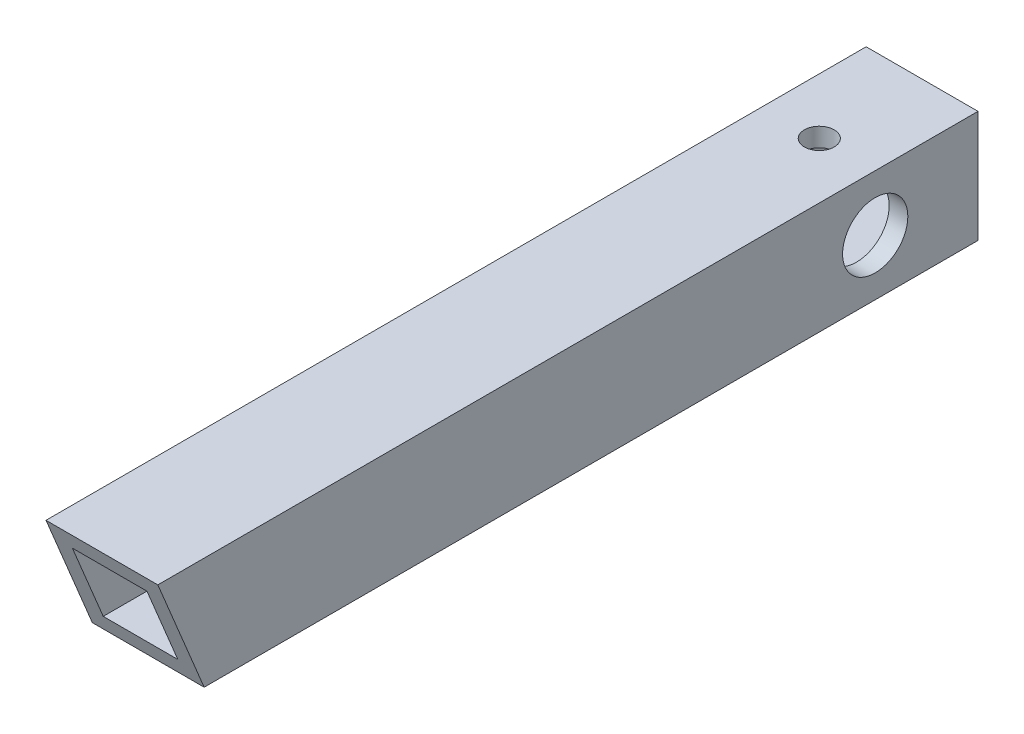
SolidWorks part; units mm, degrees
material "6061-T6 (SS)"
ref_plane "Front Plane" through (0, 0, 0) normal (0, 0, 1) x (1, 0, 0)
ref_plane "Top Plane" through (0, 0, 0) normal (0, 1, 0) x (1, 0, 0)
ref_plane "Right Plane" through (0, 0, 0) normal (1, 0, 0) x (0, 0, -1)
sketch "Sketch1" plane through (0, 0, 0) normal (0, 0, 1) x (1, 0, 0)
  line L1 (-9.525, -9.525) -> (9.525, -9.525)
  line L2 (-9.525, -9.525) -> (-9.525, 9.525)
  line L3 (-9.525, 9.525) -> (9.525, 9.525)
  line L4 (9.525, -9.525) -> (9.525, 9.525)
  line L5 (-9.525, -9.525) -> (9.525, 9.525) construction
  line L6 (-9.525, 9.525) -> (9.525, -9.525) construction
  line L7 (-6.35, -6.35) -> (6.35, -6.35)
  line L8 (-6.35, -6.35) -> (-6.35, 6.35)
  line L9 (-6.35, 6.35) -> (6.35, 6.35)
  line L10 (6.35, -6.35) -> (6.35, 6.35)
  line L11 (-6.35, -6.35) -> (6.35, 6.35) construction
  line L12 (-6.35, 6.35) -> (6.35, -6.35) construction
  point P0 (0, 0)
  point P5 (0, 0)
  dimension "D1" = 19.05
  dimension "D2" = 3.175
extrude "Boss-Extrude1" add sketch "Sketch1" along normal mid plane 139.7
sketch "Sketch2" plane through (9.525, 0, 0) normal (1, 0, 0) x (0, 0, -1)
  line L0 (-69.85, 9.525) -> (-61.9592, -9.525)
  line L1 (-69.85, -9.525) -> (69.85, -9.525) construction
  line L2 (-61.9592, -9.525) -> (-69.85, -9.525)
  line L3 (-69.85, -9.525) -> (-69.85, 9.525)
  line L7 (-69.85, -9.525) -> (-69.85, 9.525) construction
  dimension "D1" = 22.5
extrude "Cut-Extrude1" cut sketch "Sketch2" against normal through all
sketch "Sketch3" plane through (9.525, 0, 0) normal (1, 0, 0) x (0, 0, -1)
  circle A0 centre (52.3408, 0) radius 5.5562
  dimension "D1" = 11.1125
  dimension "D2" = 114.3
extrude "Cut-Extrude2" cut sketch "Sketch3" against normal through all
sketch "Sketch4" plane through (0, 9.525, 0) normal (0, 1, 0) x (1, 0, 0)
  line L0 (-9.525, 57.897) -> (-9.525, 46.7845) construction
  line L1 (-9.525, 57.897) -> (-9.525, 46.7845) construction
  line L2 (-9.525, 52.3408) -> (9.525, 52.3408) construction
  line L3 (9.525, -69.85) -> (9.525, 69.85) construction
  circle A0 centre (0, 52.3408) radius 2.54
  dimension "D1" = 5.08
extrude "Cut-Extrude3" cut sketch "Sketch4" against normal through all
